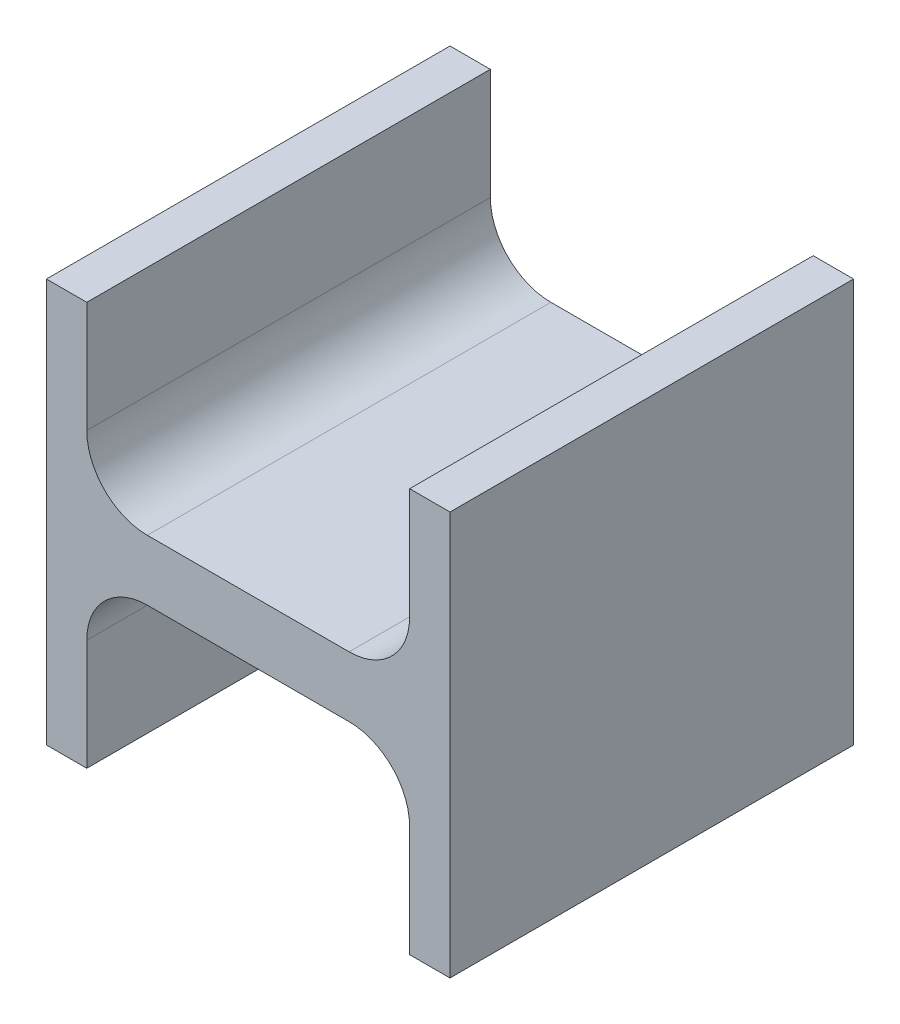
SolidWorks part; units mm, degrees
ref_plane "Front Plane" through (0, 0, 0) normal (0, 0, 1) x (1, 0, 0)
ref_plane "Top Plane" through (0, 0, 0) normal (0, 1, 0) x (1, 0, 0)
ref_plane "Right Plane" through (0, 0, 0) normal (1, 0, 0) x (0, 0, -1)
sketch "Sketch2" plane through (0, 0, 0) normal (0, 0, 1) x (1, 0, 0)
  line L0 (-10, -10) -> (-8, -10)
  line L2 (10, 10) -> (10, -10)
  line L4 (-10, 10) -> (-10, -10)
  line L5 (10, 10) -> (-10, -10) construction
  line L6 (10, -10) -> (-10, 10) construction
  line L7 (-8, -10) -> (-8, -1.5)
  line L8 (-8, -1.5) -> (8, -1.5)
  line L9 (8, -1.5) -> (8, -10)
  line L10 (8, -10) -> (10, -10)
  line L11 (-10, 10) -> (-8, 10)
  line L12 (-8, 10) -> (-8, 1.5)
  line L13 (-8, 1.5) -> (8, 1.5)
  line L14 (8, 1.5) -> (8, 10)
  line L15 (8, 10) -> (10, 10)
  point P0 (0, 0)
  point P6 (-8, -10)
  point P7 (8, -10)
  point P8 (-8, 10)
  point P9 (8, 10)
extrude "Boss-Extrude2" add sketch "Sketch2" along normal blind 20
fillet "Fillet1" radius 3 1 edges at (-8, 1.5, 10)
fillet "Fillet2" radius 3 3 edges at (-8, -1.5, 10) (8, -1.5, 10) (8, 1.5, 10)
